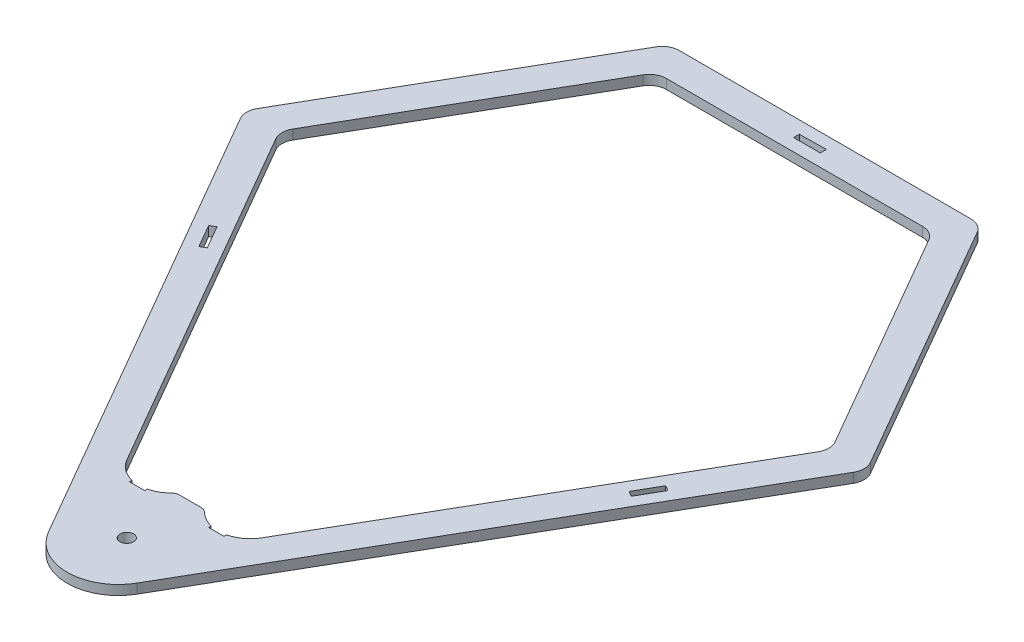
SolidWorks part; units mm, degrees
ref_plane "Front Plane" through (0, 0, 0) normal (0, 0, 1) x (1, 0, 0)
ref_plane "Top Plane" through (0, 0, 0) normal (0, 1, 0) x (1, 0, 0)
ref_plane "Right Plane" through (0, 0, 0) normal (1, 0, 0) x (0, 0, -1)
sketch "Sketch1" plane through (0, 0, 0) normal (0, 1, 0) x (1, 0, 0)
  line L0 (67.4661, -26.4094) -> (3.019, -138.0348)
  line L1 (125.3146, 73.7872) -> (44.3146, 214.0833)
  line L2 (44.3146, 214.0833) -> (-117.6854, 214.0833)
  line L3 (-117.6854, 214.0833) -> (-198.6854, 73.7872)
  line L4 (-198.6854, 73.7872) -> (-76.3899, -138.0348)
  line L6 (67.4661, -26.4094) -> (125.3146, 73.7872)
  line L7 (-36.6854, -66.5089) -> (35.4833, -66.5089) [skipped]
  line L9 (-45.2045, -140.5348) -> (-28.1664, -140.5348)
  line L11 (-36.6854, -242.805) -> (146.0992, 73.7872)
  line L12 (146.0992, 73.7872) -> (54.7069, 232.0833)
  line L13 (54.7069, 232.0833) -> (-128.0777, 232.0833)
  line L14 (-128.0777, 232.0833) -> (-219.47, 73.7872)
  line L15 (-219.47, 73.7872) -> (-36.6854, -242.805)
  line L17 (-123.23, -84.5089) -> (49.975, -84.5089) [skipped]
  line L18 (-44.5346, 224.7667) -> (-28.8363, 225)
  line L19 (-44.5346, 224.7667) -> (-44.5346, 221.4)
  line L20 (-44.5346, 221.4) -> (-28.8363, 221.4)
  line L21 (-28.8363, 225) -> (-28.8363, 221.4)
  line L22 (-171.4635, 5.0374) -> (-168.3458, 6.8374)
  line L23 (-171.4635, 5.0374) -> (-163.6135, -8.5592)
  line L24 (-163.6135, -8.5592) -> (-160.4958, -6.7592)
  line L25 (-168.3458, 6.8374) -> (-160.4958, -6.7592)
  line L26 (98.0926, 5.0374) -> (94.9749, 6.8374)
  line L27 (98.0926, 5.0374) -> (90.2426, -8.5592)
  line L28 (90.2426, -8.5592) -> (87.1249, -6.7592)
  line L29 (94.9749, 6.8374) -> (87.1249, -6.7592)
  line L31 (-64.4354, -146.9943) -> (-64.4354, -148.4943)
  line L32 (-64.4354, -148.4943) -> (-55.4354, -148.4943)
  line L33 (-55.4354, -146.9943) -> (-55.4354, -148.4943)
  line L35 (-17.9354, -146.9943) -> (-17.9354, -148.4943)
  line L36 (-17.9354, -148.4943) -> (-8.9354, -148.4943)
  line L37 (-8.9354, -146.9943) -> (-8.9354, -148.4943)
  circle A0 centre (-36.6854, 73.7872) radius 140.2961 construction
  arc A1 (-76.3899, -138.0348) -> (-64.4354, -146.9943) centre (-59.9354, -128.5348) ccw
  arc A2 (-28.1664, -140.5348) -> (-17.9354, -146.9943) centre (-13.4354, -128.5348) ccw
  circle A3 centre (-36.6854, 73.7872) radius 150 construction
  circle A4 centre (-36.6854, -177.805) radius 4
  arc A5 (-55.4354, -146.9943) -> (-45.2045, -140.5348) centre (-59.9354, -128.5348) ccw
  arc A6 (-8.9354, -146.9943) -> (3.019, -138.0348) centre (-13.4354, -128.5348) ccw
  point P37 (-169.9047, 5.9374)
  point P39 (96.5338, 5.9374)
  point P40 (-44.5346, 223.0833)
  point P41 (-36.6854, 214.0833)
  point P42 (-36.6854, 221.4)
  point P46 (0, 0)
  dimension "D2" = 38
  dimension "D3" = 38
  dimension "D8" = 8
  dimension "D4" = 46.5
  dimension "D5" = 12
  dimension "D6" = 18
  dimension "D7" = 65
  dimension "D9" = 9
  dimension "D10" = 9
  dimension "D11" = 3.6
  dimension "D12" = 15.7
  dimension "D13" = 3.6
  dimension "D14" = 15.7
  dimension "D15" = 15.7
  dimension "D16" = 3.6
  dimension "D17" = 9
  dimension "D18" = 7.85
  dimension "D19" = 7.85
  dimension "D20" = 1.5
  dimension "D21" = 9
  dimension "D22" = 9
  dimension "D23" = 1.5
  dimension "D24" = 4.5
  dimension "D25" = 4.5
  dimension "D26" = 162
extrude "Boss-Extrude1" add sketch "Sketch1" along normal blind 5.63
fillet "Fillet1" radius 10 8 edges at (-198.6854, 2.815, -73.7872) (-117.6854, 2.815, -214.0833) (44.3146, 2.815, -214.0833) (125.3146, 2.815, -73.7872) (146.0992, 2.815, -73.7872) (54.7069, 2.815, -232.0833) (-128.0777, 2.815, -232.0833) (-219.47, 2.815, -73.7872)
fillet "Fillet2" radius 30 1 edges at (-36.6854, 2.815, 242.805)
fillet "Fillet4" radius 5 2 edges at (-45.2045, 2.815, 140.5348) (-28.1664, 2.815, 140.5348)
equation "\"InnerSide\" = 162"
equation "\"Thick\" = 18"
equation "\"PropGuardRadius\"= 19"
equation "\"PropGuardDistance\"= 46.5"
equation "\"D2@Sketch1\"=\"PropGuardRadius\"*2"
equation "\"D3@Sketch1\"=\"PropGuardRadius\"*2"
equation "\"D4@Sketch1\"=\"PropGuardDistance\""
equation "\"ThickerAcrylic\"= 5.63"
equation "\"Attach width\"= 3.60"
equation "\"Attach length\"= 15.7"
equation "\"D9@Sketch1\"=\"Thick\"/2"
equation "\"D10@Sketch1\"=\"Thick\"/2"
equation "\"D11@Sketch1\"=\"Attach width\""
equation "\"D12@Sketch1\"=\"Attach length\""
equation "\"D13@Sketch1\"=\"Attach width\""
equation "\"D14@Sketch1\"=\"Attach length\""
equation "\"D15@Sketch1\"=\"Attach length\""
equation "\"D17@Sketch1\"=\"Thick\"/2"
equation "\"D18@Sketch1\"=\"Attach length\"/2"
equation "\"D19@Sketch1\"=\"Attach length\"/2"
equation "\"magnet diameter\"= 9"
equation "\"magnet depth\"= 1.5"
equation "\"D20@Sketch1\"=\"magnet depth\""
equation "\"D21@Sketch1\"=\"magnet diameter\""
equation "\"D22@Sketch1\"=\"magnet diameter\""
equation "\"D23@Sketch1\"=\"magnet depth\""
equation "\"D24@Sketch1\"=\"magnet diameter\"/2"
equation "\"D25@Sketch1\"=\"magnet diameter\"/2"
equation "\"D16@Sketch1\"=\"Attach width\""
equation "\"D26@Sketch1\"=\"InnerSide\""
equation "\"D6@Sketch1\"=\"Thick\""
